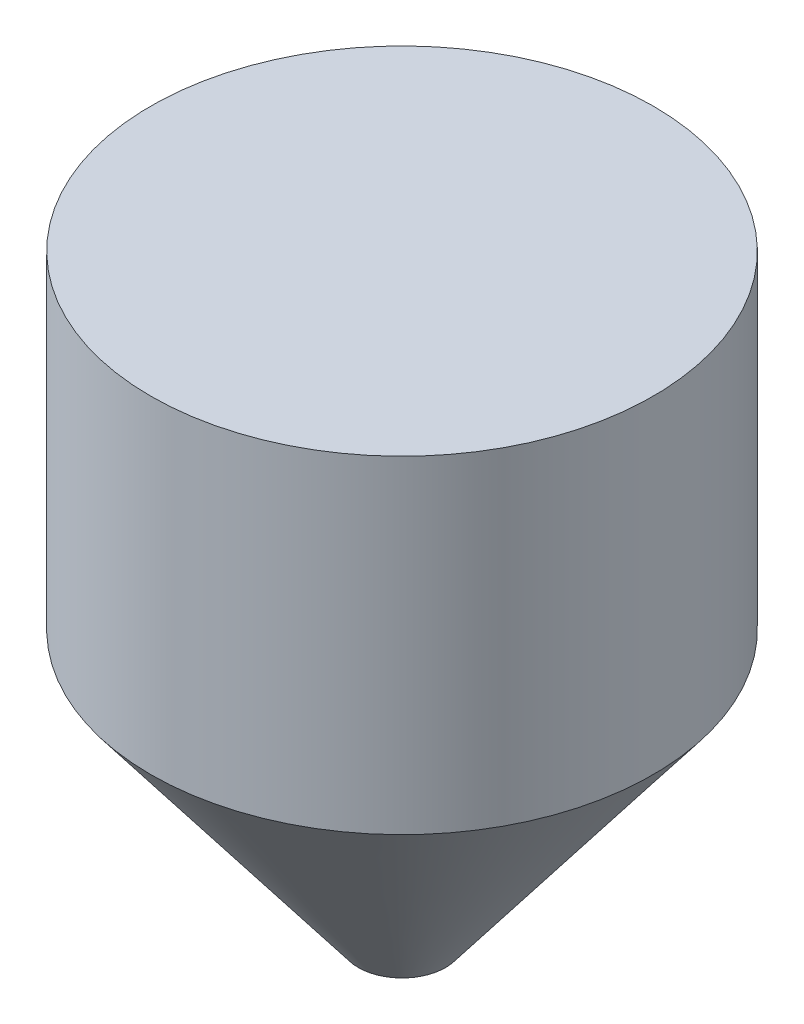
SolidWorks part; units mm, degrees
ref_plane "Alzado" through (0, 0, 0) normal (0, 0, 1) x (1, 0, 0)
ref_plane "Planta" through (0, 0, 0) normal (0, 1, 0) x (1, 0, 0)
ref_plane "Vista lateral" through (0, 0, 0) normal (1, 0, 0) x (0, 0, -1)
sketch "Croquis1" plane through (0, 0, 0) normal (0, 1, 0) x (1, 0, 0)
  circle A0 centre (0, 0) radius 115
  dimension "D1" = 230
ref_plane "Plano1" through (0, -274, 0) normal (0, 1, 0) x (1, 0, 0)
extrude "Saliente-Extruir1" add sketch "Croquis1" against normal blind 150 contours A0
sketch "Croquis2" plane through (0, -150, 0) normal (0, -1, 0) x (1, 0, 0)
  circle A1 centre (0, 0) radius 115
sketch "Croquis3" plane through (0, -274, 0) normal (0, 1, 0) x (1, 0, 0)
  circle A0 centre (0, 0) radius 20
  dimension "D1" = 40
loft "Recubrir1" add profiles "Croquis3", "Croquis2"
